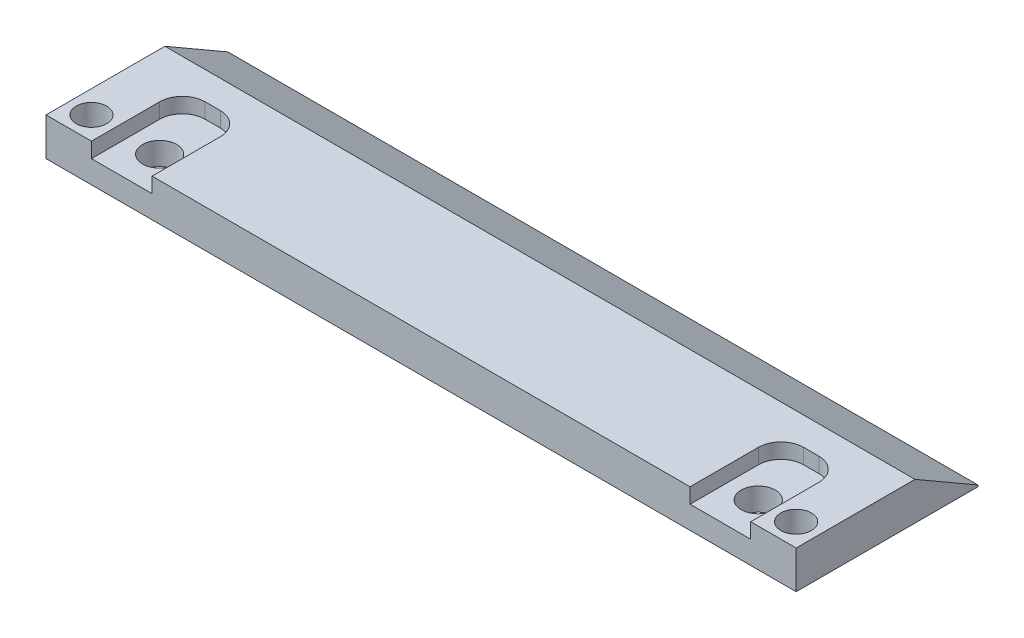
SolidWorks part; units mm, degrees
material "AISI 304"
ref_plane "Alzado" through (0, 0, 0) normal (0, 0, 1) x (1, 0, 0)
ref_plane "Planta" through (0, 0, 0) normal (0, 1, 0) x (1, 0, 0)
ref_plane "Vista lateral" through (0, 0, 0) normal (1, 0, 0) x (0, 0, -1)
sketch "Croquis1" plane through (0, 0, 0) normal (0, 1, 0) x (1, 0, 0)
  line L0 (-43.5, -12) -> (-43.5, 0)
  line L1 (-49.5, 12) -> (49.5, 12)
  line L2 (-49.5, 12) -> (-49.5, -12)
  line L3 (-49.5, -12) -> (49.5, -12)
  line L4 (49.5, 12) -> (49.5, -12)
  line L5 (-49.5, 12) -> (49.5, -12) construction
  line L6 (-49.5, -12) -> (49.5, 12) construction
  line L7 (-43.5, 0) -> (-35.5, 0)
  line L8 (-35.5, 0) -> (-35.5, -12)
  line L9 (0, 0) -> (0, -6.9349) construction
  line L10 (35.5, 0) -> (35.5, -12)
  line L12 (43.5, -12) -> (43.5, 0)
  circle A0 centre (-46.5, -9) radius 2.0175
  circle A1 centre (-39.5, -7) radius 2.25
  circle A2 centre (39.5, -7) radius 2.25
  circle A3 centre (46.5, -9) radius 2.0175
  point P0 (0, 0)
  dimension "D9" = 4.5
  dimension "D1" = 24
  dimension "D2" = 99
  dimension "D3" = 3
  dimension "D4" = 3
  dimension "D5" = 6
  dimension "D6" = 8
  dimension "D7" = 12
  dimension "D8" = 2
extrude "Saliente-Extruir1" add sketch "Croquis1" along normal blind 5
sketch "Croquis2" plane through (0, 5, 0) normal (0, 1, 0) x (1, 0, 0)
  line L0 (-49.5, -12) -> (49.5, -12) construction
  line L2 (-43.5, -3) -> (-43.5, -12)
  line L3 (-43.5, -12) -> (-35.5, -12)
  line L4 (-35.5, -3) -> (-35.5, -12)
  line L5 (0, 0) -> (0, -5.1087) construction
  line L6 (40.5, 0) -> (38.5, 0)
  line L7 (-40.5, 0) -> (-38.5, 0)
  line L8 (35.5, -3) -> (35.5, -12)
  line L9 (43.5, -12) -> (35.5, -12)
  line L10 (43.5, -3) -> (43.5, -12)
  arc A0 (-38.5, 0) -> (-35.5, -3) centre (-38.5, -3) cw
  arc A1 (-40.5, 0) -> (-43.5, -3) centre (-40.5, -3) ccw
  arc A2 (38.5, 0) -> (35.5, -3) centre (38.5, -3) ccw
  arc A3 (40.5, 0) -> (43.5, -3) centre (40.5, -3) cw
  point P0 (-39.5, -7)
  point P15 (39.5, -7)
  point P18 (-35.5, 0)
  point P21 (-43.5, 0)
  dimension "D3" = 3
  dimension "D1" = 8
  dimension "D2" = 4
extrude "Cortar-Extruir1" cut sketch "Croquis2" against normal blind 2
sketch "Croquis3" plane through (-49.5, 0, 0) normal (-1, 0, 0) x (0, 0, 1)
  line L0 (-12, 0) -> (-12, 0.2)
  line L1 (-12, 5) -> (-12, 0) construction
  line L2 (-12, 0.2) -> (-6.1009, 3.6058)
  line L3 (-12, 0) -> (-5.7905, 0)
  line L4 (-12, 0) -> (12, 0) construction
  line L5 (-6.1009, 3.6058) -> (-3.0399, 5.3731)
  line L6 (-3.0399, 5.3731) -> (-12.7572, 5.3731)
  line L7 (-12.7572, 5.3731) -> (-12.7572, 0.2)
  line L8 (-12.7572, 0.2) -> (-12, 0.2)
  line M10 (12, 5) -> (-12, 5)
  line M11 (-12, 5) -> (-12, 0)
  dimension "D1" = 0.2
  dimension "D2" = 30
extrude "Cortar-Extruir5" cut sketch "Croquis3" against normal blind 141 contours L2 L5 M10 M11 | L7 L8 L5 L6 M11 M10
